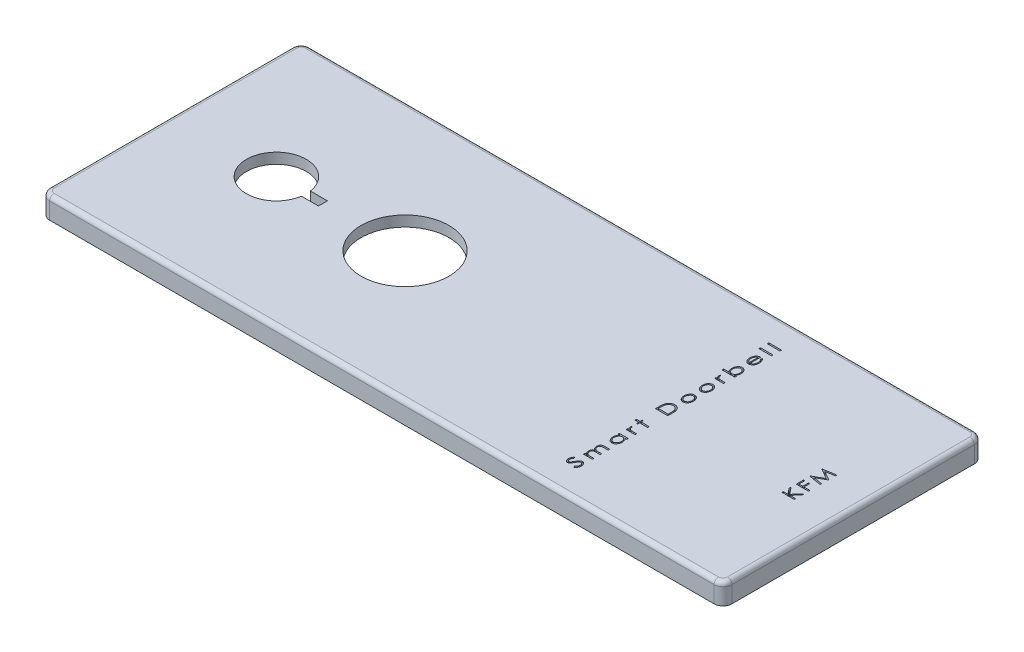
SolidWorks part; units mm, degrees
ref_plane "Front Plane" through (0, 0, 0) normal (0, 0, 1) x (1, 0, 0)
ref_plane "Top Plane" through (0, 0, 0) normal (0, 1, 0) x (1, 0, 0)
ref_plane "Right Plane" through (0, 0, 0) normal (1, 0, 0) x (0, 0, -1)
sketch "Sketch1" plane through (0, 0, 0) normal (0, 1, 0) x (1, 0, 0)
  line L1 (-97, -37) -> (97, -37)
  line L2 (-97, -37) -> (-97, 37)
  line L3 (-97, 37) -> (97, 37)
  line L4 (97, -37) -> (97, 37)
  line L5 (-97, -37) -> (97, 37) construction
  line L6 (-97, 37) -> (97, -37) construction
  point P0 (0, 0)
  dimension "D1" = 194
  dimension "D2" = 74
extrude "Boss-Extrude1" add sketch "Sketch1" along normal blind 6
sketch "Sketch2" plane through (0, 6, 0) normal (0, 1, 0) x (1, 0, 0)
  line L3 (-97, 37) -> (-97, -37) construction
  line L5 (-63.2317, -1.2767) -> (-53.7683, -1.2767)
  line L6 (-63.2317, -1.2767) -> (-63.2317, 1.2767)
  line L7 (-63.2317, 1.2767) -> (-53.7683, 1.2767)
  line L8 (-53.7683, -1.2767) -> (-53.7683, 1.2767)
  line L9 (-63.2317, -1.2767) -> (-53.7683, 1.2767) construction
  line L10 (-63.2317, 1.2767) -> (-53.7683, -1.2767) construction
  circle A0 centre (-67, 0) radius 8.5
  circle A1 centre (-30.4154, 0) radius 12.5
  point P6 (-75.5, 0)
  point P8 (-58.5, 0)
  dimension "D3" = 25
  dimension "D4" = 17
  dimension "D1" = 30
  dimension "D2" = 36.5846
fillet "Fillet1" radius 2.54 4 edges at (-97, 3, -37) (97, 3, -37) (97, 3, 37) (-97, 3, 37)
sketch "Sketch7" plane through (0, 0, 0) normal (0, -1, 0) x (1, 0, 0)
  line L1 (-96, 36) -> (96, 36)
  line L2 (-96, 36) -> (-96, -36)
  line L3 (-96, -36) -> (96, -36)
  line L4 (96, 36) -> (96, -36)
  line L5 (-96, 36) -> (96, -36) construction
  line L6 (-96, -36) -> (96, 36) construction
  point P0 (0, 0)
  dimension "D1" = 192
  dimension "D2" = 72
extrude "Cut-Extrude3" cut sketch "Sketch7" against normal blind 3
fillet "Fillet2" radius 2.54 4 edges at (-96, 1.5, -36) (-96, 1.5, 36) (96, 1.5, -36) (96, 1.5, 36)
fillet "Fillet3" radius 1.27 8 edges at (-96.2561, 6, 36.2561) (-96.2561, 6, -36.2561) (96.2561, 6, -36.2561) (96.2561, 6, 36.2561) (97, 6, 0) (0, 6, -37) (-97, 6, 0) (0, 6, 37)
extrude "Cut-Extrude4" cut sketch "Sketch2" against normal blind 8.3855 contours L7 A0 L5 L6 | L5 A0 L7 L6 | A0 L5 L8 L7 | A1
sketch "Sketch11" plane through (0, 6, 0) normal (0, 1, 0) x (1, 0, 0)
  line L0 (47.5642, -35.73) -> (47.5642, 35.73) construction
  line L1 (-94.46, -35.73) -> (94.46, -35.73) construction
  line L2 (94.46, 35.73) -> (-94.46, 35.73) construction
  line L3 (86.1635, -35.73) -> (86.1635, 35.73) construction
  text T0 "Smart Doorbell" font "Century Gothic" height 3.5
  text T1 "KFM" font "Century Gothic" height 3.5
extrude "Cut-Extrude6" cut sketch "Sketch11" against normal blind 2.54
